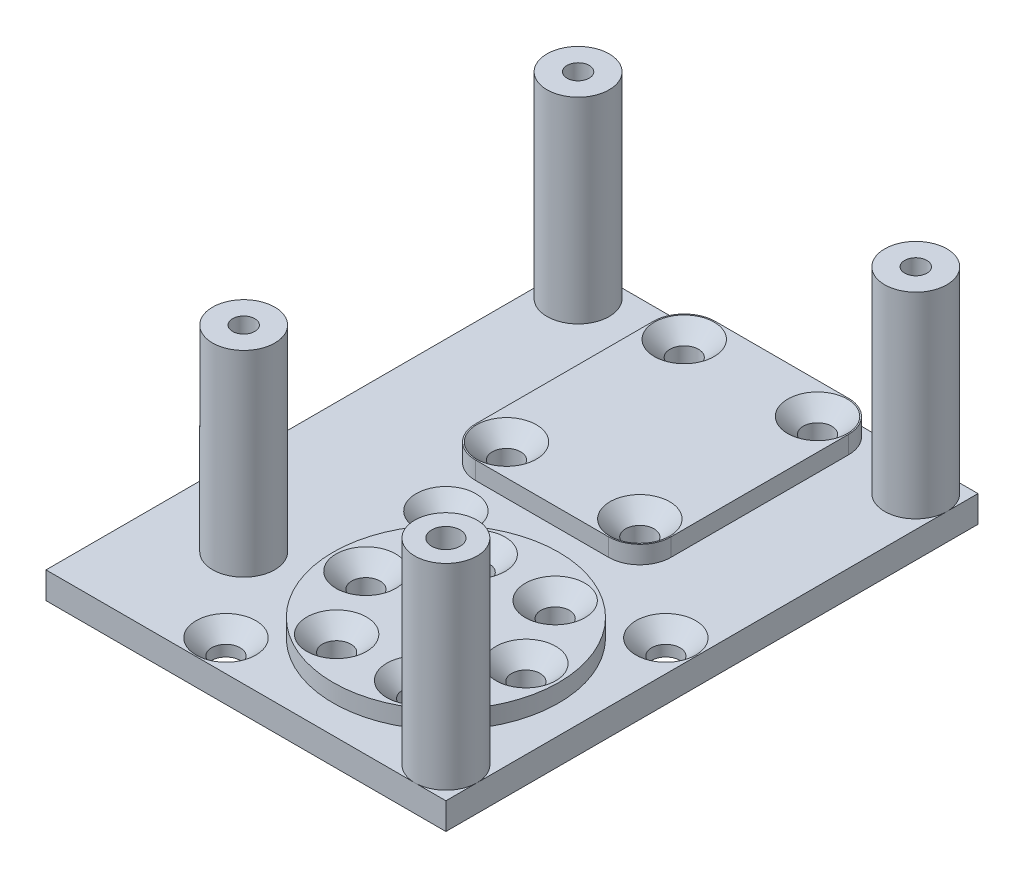
SolidWorks part; units mm, degrees
material "6061-T6 (SS)"
ref_plane "Front Plane" through (0, 0, 0) normal (0, 0, 1) x (1, 0, 0)
ref_plane "Top Plane" through (0, 0, 0) normal (0, 1, 0) x (1, 0, 0)
ref_plane "Right Plane" through (0, 0, 0) normal (1, 0, 0) x (0, 0, -1)
sketch "Chube Spacing" plane through (0, 0, 0) normal (0, 1, 0) x (1, 0, 0)
  line L0 (0, 0) -> (-9, 0) construction
  line L1 (0, 0) -> (-4.5, 7.7942) construction
  circle A0 centre (0, 0) radius 9 construction
  circle A1 centre (0, 0) radius 12.7
  circle A2 centre (0, 0) radius 2
  point P3 (-9, 0)
  point P6 (-4.5, 7.7942)
  point P9 (4.5, 7.7942)
  point P10 (9, 0)
  point P11 (4.5, -7.7942)
  point P12 (-4.5, -7.7942)
  dimension "D1" = 18
  dimension "D2" = 25.4
  dimension "D5" = 4
  dimension "D4" = 60
  dimension "D3" = 6
sketch "Sketch2" plane through (0, 0, 0) normal (0, 1, 0) x (1, 0, 0)
  line L0 (12.3744, -12.3744) -> (0, 0) construction
  line L1 (-29.1256, -15.8744) -> (15.8744, -15.8744)
  line L2 (-29.1256, -15.8744) -> (-29.1256, 44)
  line L3 (-29.1256, 44) -> (15.8744, 44)
  line L4 (15.8744, -15.8744) -> (15.8744, 44)
  circle A1 centre (12.3744, -12.3744) radius 3.5 construction
  dimension "D5" = 7
  dimension "D2" = 44
  dimension "D3" = 45
  dimension "D6" = 17.5
  dimension "D7" = 45
extrude "Main Extrude" add sketch "Sketch2" along normal blind 3
hole_wizard "Bowden Hole" positions "Sketch5" profile "Sketch6" hole size "Ø4.0" standard "ANSI Metric" end condition up to next
sketch "Sketch5" plane through (0, 3, 0) normal (0, 1, 0) x (1, 0, 0)
  point P0 (0, 0)
sketch "Sketch6" plane through (0, 3, 0) normal (1, 0, 0) x (0, 0, 1)
  line L0 (0, 0) -> (0, 3)
  line L1 (0, 3) -> (2, 3)
  line L2 (2, 3) -> (2, 0)
  line L5 (2, 0) -> (0, 0)
  line L11 (0, -6.35) -> (0, 107.95) construction
  dimension "Thru Hole Dia." = 4
  dimension "Thru Hole Depth" = 3
sketch "Sketch7" plane through (0, 3, 0) normal (0, 1, 0) x (1, 0, 0)
  line L0 (15.8744, 44) -> (-29.1256, 44) construction
  line L1 (-29.1256, 44) -> (-29.1256, -15.8744) construction
  line L2 (15.8744, -15.8744) -> (15.8744, 44) construction
  line L3 (-29.1256, -15.8744) -> (15.8744, -15.8744) construction
  circle A0 centre (-25.6256, 40.5) radius 3.5
  circle A1 centre (12.3744, 40.5) radius 3.5
  circle A2 centre (-19.7613, -2.9933) radius 3.5
  circle A3 centre (12.3744, -12.3744) radius 3.5
  point P0 (-25.6256, 40.5)
  point P3 (-19.7613, -2.9933)
  point P7 (-19.7613, -2.9933)
  dimension "D4" = 7
extrude "Spacer Pillars" add sketch "Sketch7" along normal blind 22.1
hole_wizard "Top Threads" positions "Sketch8" profile "Sketch9" hole size "M3x0.5" standard "ANSI Metric"
sketch "Sketch8" plane through (0, 25.1, 0) normal (0, 1, 0) x (1, 0, 0)
  point P3 (12.3744, 40.5)
  point P7 (-19.7613, -2.9933)
  point P17 (-25.6256, 40.5)
sketch "Sketch9" plane through (12.3744, 25.1, -40.5) normal (1, 0, 0) x (0, 0, 1)
  line L0 (0, 0) -> (0, 10.7511)
  line L1 (0, 10.7511) -> (1.25, 10)
  line L2 (1.25, 10) -> (1.25, 0)
  line L5 (1.25, 0) -> (0, 0)
  line L10 (0, 10.7511) -> (-1.25, 10) construction
  line L11 (0, -6.35) -> (0, 107.95) construction
  dimension "Hole Dia." = 2.5
  dimension "Hole Depth" = 10
  dimension "Drill Angle" = 118
hole_wizard "Top Through Hole" positions "Sketch26" profile "Sketch27" hole size "M3" standard "ANSI Metric" end condition up to next
sketch "Sketch26" plane through (0, 25.1, 0) normal (0, 1, 0) x (1, 0, 0)
  point P0 (12.3744, -12.3744)
sketch "Sketch27" plane through (12.3744, 25.1, 12.3744) normal (1, 0, 0) x (0, 0, 1)
  line L0 (0, 0) -> (0, 25.1)
  line L1 (0, 25.1) -> (1.6, 25.1)
  line L2 (1.6, 25.1) -> (1.6, 0)
  line L5 (1.6, 0) -> (0, 0)
  line L11 (0, -6.35) -> (0, 107.95) construction
  dimension "Thru Hole Dia." = 3.2
  dimension "Thru Hole Depth" = 25.1
sketch "Sketch28" plane through (0, 3, 0) normal (0, 1, 0) x (1, 0, 0)
  circle A0 centre (0, 0) radius 12.7
  circle A1 centre (0, 0) radius 2
  circle A2 centre (0, 0) radius 2 construction
  dimension "D1" = 25.4
extrude "Boss-Extrude3" add sketch "Sketch28" along normal blind 2
hole_wizard "Chube Mounting" positions "Sketch3" profile "Sketch4" countersink size "M3" standard "ANSI Metric" end condition up to next
sketch "Sketch3" plane through (0, 5, 0) normal (0, 1, 0) x (1, 0, 0)
  point P0 (-4.5, 7.7942)
  point P3 (4.5, 7.7942)
  point P6 (9, 0)
  point P9 (4.5, -7.7942)
  point P12 (-4.5, -7.7942)
  point P15 (-9, 0)
sketch "Sketch4" plane through (-4.5, 5, -7.7942) normal (1, 0, 0) x (0, 0, 1)
  line L0 (0, 0) -> (0, 5)
  line L1 (0, 5) -> (1.6, 5)
  line L2 (1.6, 5) -> (1.6, 1.76)
  line L3 (1.6, 1.76) -> (3.36, 0)
  line L5 (3.36, 0) -> (0, 0)
  line L6 (-1.6, 1.76) -> (-3.36, 0) construction
  line L11 (0, -6.35) -> (0, 107.95) construction
  dimension "Thru Hole Dia." = 3.2
  dimension "Thru Hole Depth" = 5
  dimension "Near C'Sink Dia." = 6.72
  dimension "Near C'Sink Angle" = 90
sketch "MGN12C Holes" plane through (0, 3, 0) normal (0, 1, 0) x (1, 0, 0)
  line L0 (12.3744, 44) -> (-25.6256, 44) construction
  line L1 (11.3184, 17) -> (-23.6816, 17)
  line L2 (11.3184, 17) -> (11.3184, 44)
  line L3 (11.3184, 44) -> (-23.6816, 44)
  line L4 (-23.6816, 17) -> (-23.6816, 44)
  line L5 (11.3184, 17) -> (-23.6816, 44) construction
  line L6 (11.3184, 44) -> (-23.6816, 17) construction
  line L7 (1.3184, 20.5) -> (-13.6816, 20.5)
  line L8 (1.3184, 20.5) -> (1.3184, 40.5)
  line L9 (1.3184, 40.5) -> (-13.6816, 40.5)
  line L10 (-13.6816, 20.5) -> (-13.6816, 40.5)
  line L11 (1.3184, 20.5) -> (-13.6816, 40.5) construction
  line L12 (1.3184, 40.5) -> (-13.6816, 20.5) construction
  circle A1 centre (-13.6816, 40.5) radius 3.5
  circle A2 centre (1.3184, 40.5) radius 3.5
  circle A3 centre (1.3184, 20.5) radius 3.5
  circle A4 centre (-13.6816, 20.5) radius 3.5
  circle A5 centre (0, 0) radius 16
  point P3 (-6.1816, 30.5)
  point P8 (-6.1816, 30.5)
  dimension "D1" = 32
  dimension "D6" = 7
  dimension "D2" = 35
  dimension "D3" = 27
  dimension "D4" = 15
  dimension "D5" = 20
sketch "Sketch29" plane through (0, 3, 0) normal (0, 1, 0) x (1, 0, 0)
  line L0 (-17.1816, 40.5) -> (-17.1816, 20.5)
  line L1 (-13.6816, 17) -> (1.3184, 17)
  line L2 (4.8184, 20.5) -> (4.8184, 40.5)
  line L3 (1.3184, 44) -> (-13.6816, 44)
  circle A0 centre (1.3184, 20.5) radius 3.5 construction
  circle A1 centre (-13.6816, 20.5) radius 3.5 construction
  circle A2 centre (1.3184, 40.5) radius 3.5 construction
  circle A3 centre (-13.6816, 40.5) radius 3.5 construction
  arc A4 (1.3184, 17) -> (4.8184, 20.5) centre (1.3184, 20.5) ccw
  arc A5 (-17.1816, 20.5) -> (-13.6816, 17) centre (-13.6816, 20.5) ccw
  arc A6 (4.8184, 40.5) -> (1.3184, 44) centre (1.3184, 40.5) ccw
  arc A7 (-13.6816, 44) -> (-17.1816, 40.5) centre (-13.6816, 40.5) ccw
extrude "Boss-Extrude4" add sketch "Sketch29" along normal blind 2
hole_wizard "Carriage Holes" positions "Sketch11" profile "Sketch12" countersink size "M3" standard "ANSI Metric"
sketch "Sketch11" plane through (0, 5, 0) normal (0, 1, 0) x (1, 0, 0)
  point P3 (1.3184, 40.5)
  point P6 (1.3184, 20.5)
  point P9 (-13.6816, 20.5)
  point P15 (-13.6816, 40.5)
sketch "Sketch12" plane through (1.3184, 5, -40.5) normal (1, 0, 0) x (0, 0, 1)
  line L0 (0, 0) -> (0, 8.9614)
  line L1 (0, 8.9614) -> (1.6, 8)
  line L2 (1.6, 8) -> (1.6, 1.76)
  line L3 (1.6, 1.76) -> (3.36, 0)
  line L5 (3.36, 0) -> (0, 0)
  line L6 (-1.6, 1.76) -> (-3.36, 0) construction
  line L10 (0, 8.9614) -> (-1.6, 8) construction
  line L11 (0, -6.35) -> (0, 107.95) construction
  dimension "Hole Dia." = 3.2
  dimension "Hole Depth" = 8
  dimension "Near C'Sink Dia." = 6.72
  dimension "Near C'Sink Angle" = 90
  dimension "Drill Angle" = 118
sketch "Beacon SLM Support Mounting Positions" plane through (0, 3, 0) normal (0, 1, 0) x (1, 0, 0)
  line L0 (-12.3744, 12.3744) -> (0, 0) construction
  line L1 (0, 0) -> (12.3744, 12.3744) construction
  line L2 (0, 0) -> (-12.3744, -12.3744) construction
  dimension "D1" = 17.5
hole_wizard "Beacon SLM Support Holes" positions "Sketch24" profile "Sketch25" countersink size "M3" standard "ANSI Metric" end condition through all
sketch "Sketch24" plane through (0, 3, 0) normal (0, 1, 0) x (1, 0, 0)
  point P0 (-12.3744, 12.3744)
  point P3 (12.3744, 12.3744)
  point P7 (-12.3744, -12.3744)
sketch "Sketch25" plane through (-12.3744, 3, -12.3744) normal (1, 0, 0) x (0, 0, 1)
  line L0 (0, 0) -> (0, 3)
  line L1 (0, 3) -> (1.6, 3)
  line L2 (1.6, 3) -> (1.6, 1.76)
  line L3 (1.6, 1.76) -> (3.36, 0)
  line L5 (3.36, 0) -> (0, 0)
  line L6 (-1.6, 1.76) -> (-3.36, 0) construction
  line L11 (0, -6.35) -> (0, 107.95) construction
  dimension "Thru Hole Dia." = 3.2
  dimension "Thru Hole Depth" = 3
  dimension "Near C'Sink Dia." = 6.72
  dimension "Near C'Sink Angle" = 90
sketch "CPAP Duct Location" plane through (0, 3, 0) normal (0, 1, 0) x (1, 0, 0)
  line L0 (0, -25) -> (0, 0) construction
  circle A0 centre (0, -25) radius 9
  circle A1 centre (0, -25) radius 7.5
  dimension "D1" = 18
  dimension "D2" = 1.5
  dimension "D3" = 25
